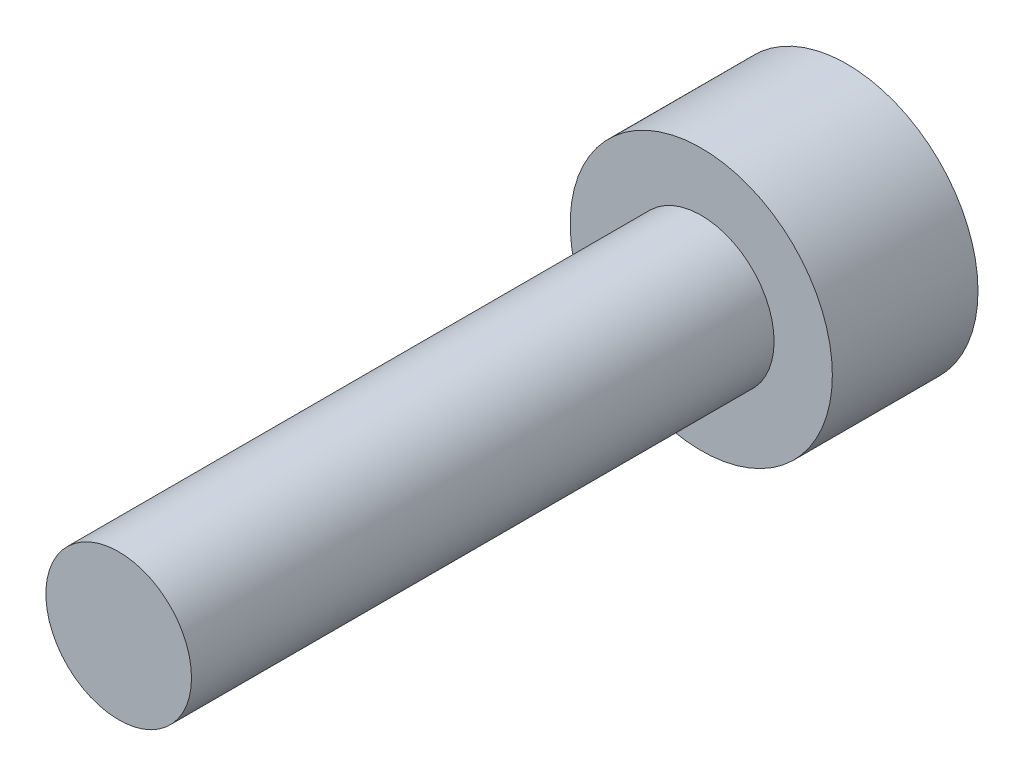
SolidWorks part; units mm, degrees
material "AISI 304"
ref_plane "前视基准面" through (0, 0, 0) normal (0, 0, 1) x (1, 0, 0)
ref_plane "上视基准面" through (0, 0, 0) normal (0, 1, 0) x (1, 0, 0)
ref_plane "右视基准面" through (0, 0, 0) normal (1, 0, 0) x (0, 0, -1)
sketch "草图1" plane through (0, 0, 0) normal (0, 0, 1) x (1, 0, 0)
  circle A0 centre (0, 0) radius 2.25
  dimension "D1" = 4.5
extrude "凸台-拉伸1" add sketch "草图1" along normal blind 2.5
sketch "草图2" plane through (0, 0, 2.5) normal (0, 0, 1) x (1, 0, 0)
  circle A0 centre (0, 0) radius 1.25
  dimension "D1" = 2.5
extrude "凸台-拉伸2" add sketch "草图2" along normal blind 10
cosmetic thread "装饰螺纹线1" parameters "D2"=2.013
sketch "草图3" plane through (0, 0, 0) normal (0, 0, -1) x (-1, 0, 0)
  line L1 (1.1547, 0) -> (0.5774, 1)
  line L2 (0.5774, 1) -> (-0.5774, 1)
  line L3 (-0.5774, 1) -> (-1.1547, 0)
  line L4 (-1.1547, 0) -> (-0.5774, -1)
  line L5 (-0.5774, -1) -> (0.5774, -1)
  line L6 (0.5774, -1) -> (1.1547, 0)
  circle A0 centre (0, 0) radius 1 construction
  dimension "D1" = 2
extrude "切除-拉伸1" cut sketch "草图3" against normal blind 1
